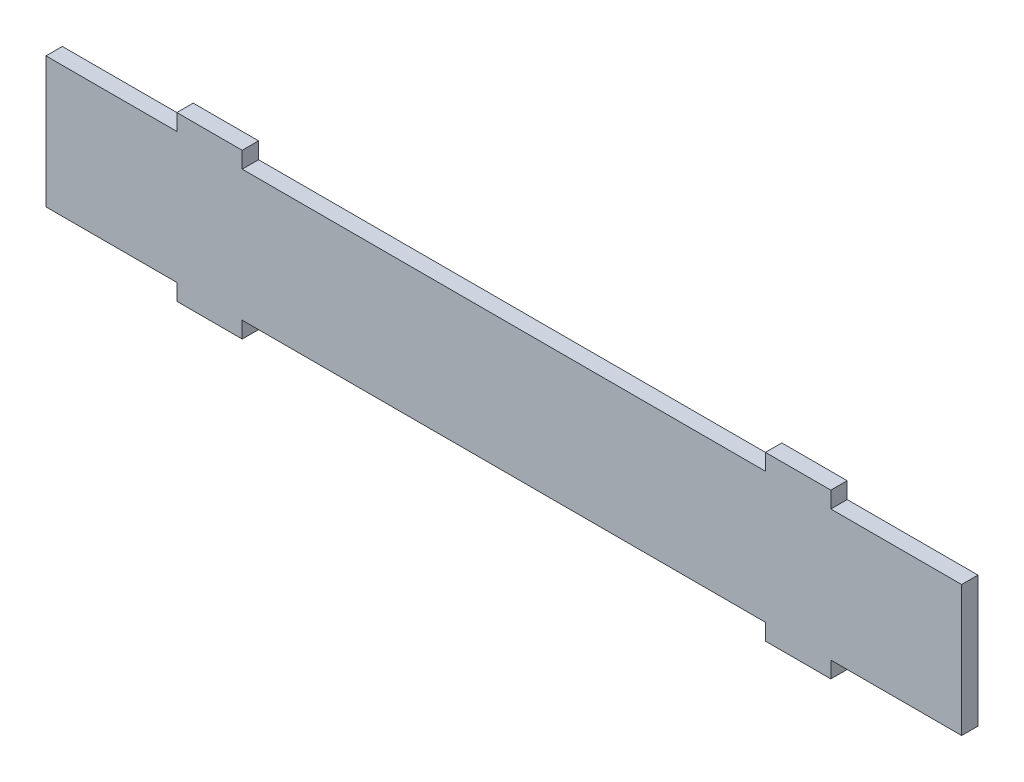
SolidWorks part; units mm, degrees
ref_plane "Front Plane" through (0, 0, 0) normal (0, 0, 1) x (1, 0, 0)
ref_plane "Top Plane" through (0, 0, 0) normal (0, 1, 0) x (1, 0, 0)
ref_plane "Right Plane" through (0, 0, 0) normal (1, 0, 0) x (0, 0, -1)
sketch "Sketch1" plane through (0, 0, 0) normal (0, 0, 1) x (1, 0, 0)
  line L1 (0, 0) -> (177.8, 0)
  line L2 (0, 0) -> (0, 25.4)
  line L3 (0, 25.4) -> (177.8, 25.4)
  line L4 (177.8, 0) -> (177.8, 25.4)
  dimension "D1" = 177.8
  dimension "D2" = 25.4
extrude "Boss-Extrude1" add sketch "Sketch1" along normal blind 3.175
sketch "Sketch2" plane through (0, 25.4, 0) normal (0, 1, 0) x (1, 0, 0)
  line L0 (177.8, 0) -> (0, 0) construction
  line L1 (25.4, 0) -> (38.1, 0)
  line L2 (25.4, 0) -> (25.4, -3.175)
  line L3 (25.4, -3.175) -> (38.1, -3.175)
  line L4 (38.1, 0) -> (38.1, -3.175)
  line L5 (177.8, -3.175) -> (0, -3.175) construction
  line L6 (0, -3.175) -> (0, 0) construction
  line L7 (139.7, 0) -> (152.4, 0)
  line L8 (139.7, 0) -> (139.7, -3.175)
  line L9 (139.7, -3.175) -> (152.4, -3.175)
  line L10 (152.4, 0) -> (152.4, -3.175)
  line L11 (177.8, -3.175) -> (177.8, 0) construction
  dimension "D1" = 12.7
  dimension "D2" = 12.7
  dimension "D3" = 25.4
  dimension "D4" = 25.4
extrude "Boss-Extrude2" add sketch "Sketch2" along normal blind 3.175
sketch "Sketch3" plane through (0, 0, 0) normal (0, -1, 0) x (1, 0, 0)
  line L0 (0, 3.175) -> (177.8, 3.175) construction
  line L1 (25.4, 3.175) -> (38.1, 3.175)
  line L2 (25.4, 3.175) -> (25.4, 0)
  line L3 (25.4, 0) -> (38.1, 0)
  line L4 (38.1, 3.175) -> (38.1, 0)
  line L5 (0, 0) -> (177.8, 0) construction
  line L6 (0, 3.175) -> (0, 0) construction
  line L7 (139.7, 3.175) -> (152.4, 3.175)
  line L8 (139.7, 3.175) -> (139.7, 0)
  line L9 (139.7, 0) -> (152.4, 0)
  line L10 (152.4, 3.175) -> (152.4, 0)
  line L11 (177.8, 3.175) -> (177.8, 0) construction
  point P15 (177.8, 1.5875)
  dimension "D1" = 12.7
  dimension "D2" = 12.7
  dimension "D3" = 25.4
  dimension "D4" = 25.4
extrude "Boss-Extrude3" add sketch "Sketch3" along normal blind 3.175
